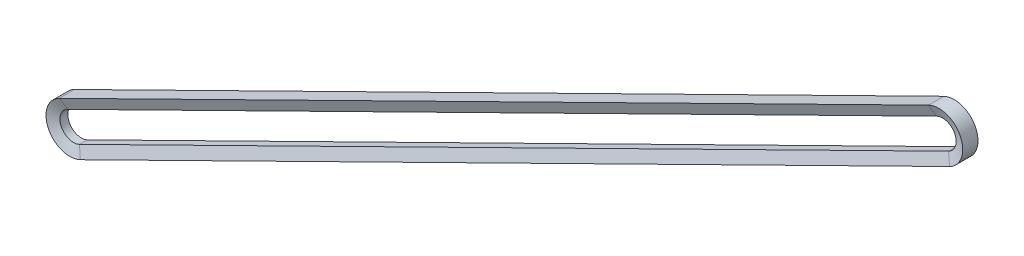
SolidWorks part; units mm, degrees
ref_plane "前视基准面" through (0, 0, 0) normal (0, 0, 1) x (1, 0, 0)
ref_plane "上视基准面" through (0, 0, 0) normal (0, 1, 0) x (1, 0, 0)
ref_plane "右视基准面" through (0, 0, 0) normal (1, 0, 0) x (0, 0, -1)
sketch "草图2" plane through (0, 0, 0) normal (0, 0, 1) x (1, 0, 0)
  line L0 (0, 0) -> (1, 0) construction
  line L1 (0, 0) -> (0, 1) construction
  line L2 (2.3443, -4.7533) -> (-337.4292, -172.328)
  line L3 (-342.1178, -162.8213) -> (-2.3443, 4.7533)
  arc A0 (-2.3443, 4.7533) -> (2.3443, -4.7533) centre (0, 0) cw
  arc A1 (-337.4292, -172.328) -> (-342.1178, -162.8213) centre (-339.7735, -167.5747) cw
ref_plane "基准面4" through (0, 0, 0) normal (0.8969, 0.4423, 0) x (0, 0, -1)
sketch "草图3" plane through (0, 0, 0) normal (0.8969, 0.4423, 0) x (0, 0, -1)
  line L0 (-1.535, 5.3) -> (1.535, 5.3)
  line L1 (0, 5.3) -> (0, -5.3) construction
  line L2 (1.535, 5.3) -> (2.9909, 9.3)
  line L3 (0, 5.3) -> (0, 9.3)
  line L4 (-2.9909, 9.3) -> (2.9909, 9.3)
  line L5 (-1.535, 5.3) -> (-2.9909, 9.3)
  dimension "D1" = 110
sweep "扫描1" add profiles "草图3" path "草图2"
